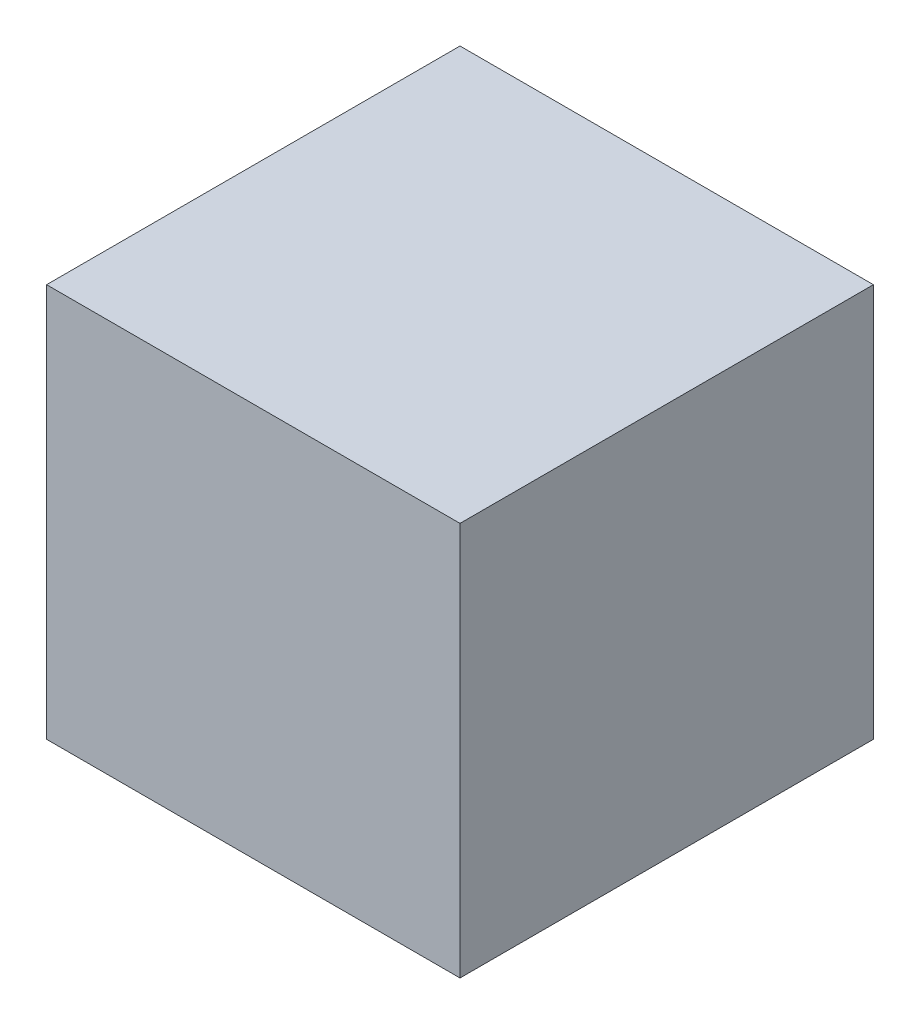
SolidWorks part; units mm, degrees
ref_plane "Front Plane" through (0, 0, 0) normal (0, 0, 1) x (1, 0, 0)
ref_plane "Top Plane" through (0, 0, 0) normal (0, 1, 0) x (1, 0, 0)
ref_plane "Right Plane" through (0, 0, 0) normal (1, 0, 0) x (0, 0, -1)
sketch "Sketch1" plane through (0, 0, 0) normal (0, 1, 0) x (1, 0, 0)
  line L1 (0, 0) -> (42, 0)
  line L2 (0, 0) -> (0, 42)
  line L3 (0, 42) -> (42, 42)
  line L4 (42, 0) -> (42, 42)
extrude "Boss-Extrude1" add sketch "Sketch1" along normal blind 40
